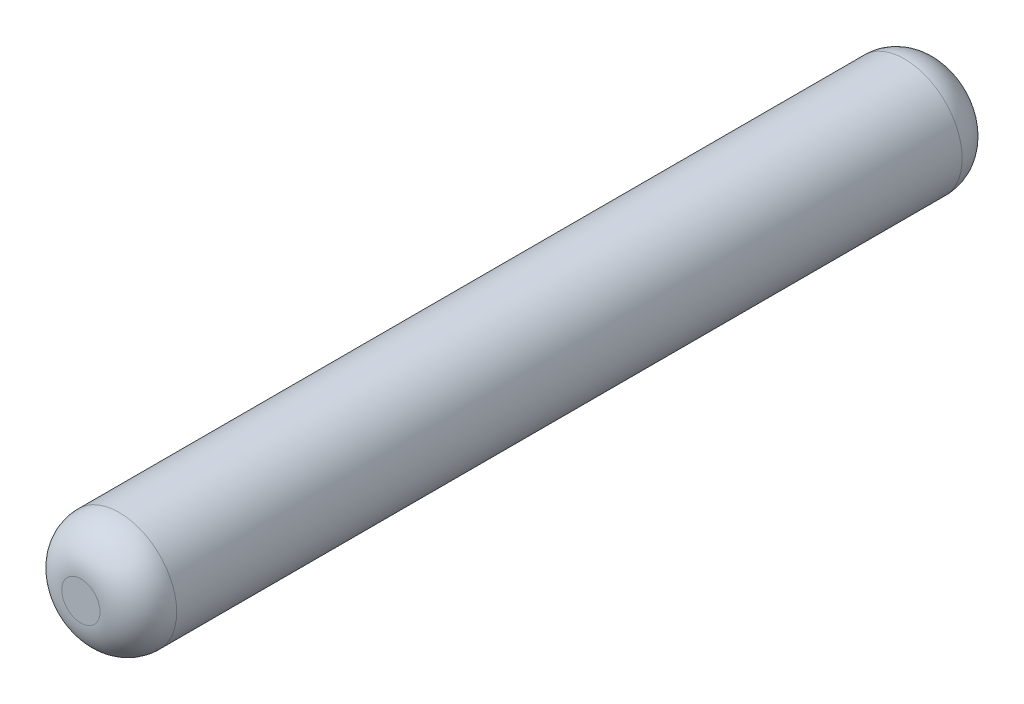
SolidWorks part; units mm, degrees
material "Alumina"
ref_plane "Front Plane" through (0, 0, 0) normal (0, 0, 1) x (1, 0, 0)
ref_plane "Top Plane" through (0, 0, 0) normal (0, 1, 0) x (1, 0, 0)
ref_plane "Right Plane" through (0, 0, 0) normal (1, 0, 0) x (0, 0, -1)
sketch "Sketch1" plane through (0, 0, 0) normal (0, 0, 1) x (1, 0, 0)
  circle A0 centre (0, 0) radius 3
  dimension "D1" = 6
extrude "Boss-Extrude1" add sketch "Sketch1" along normal blind 45
fillet "Fillet1" radius 2 2 edges at (3, 0, 0) (3, 0, 45)
